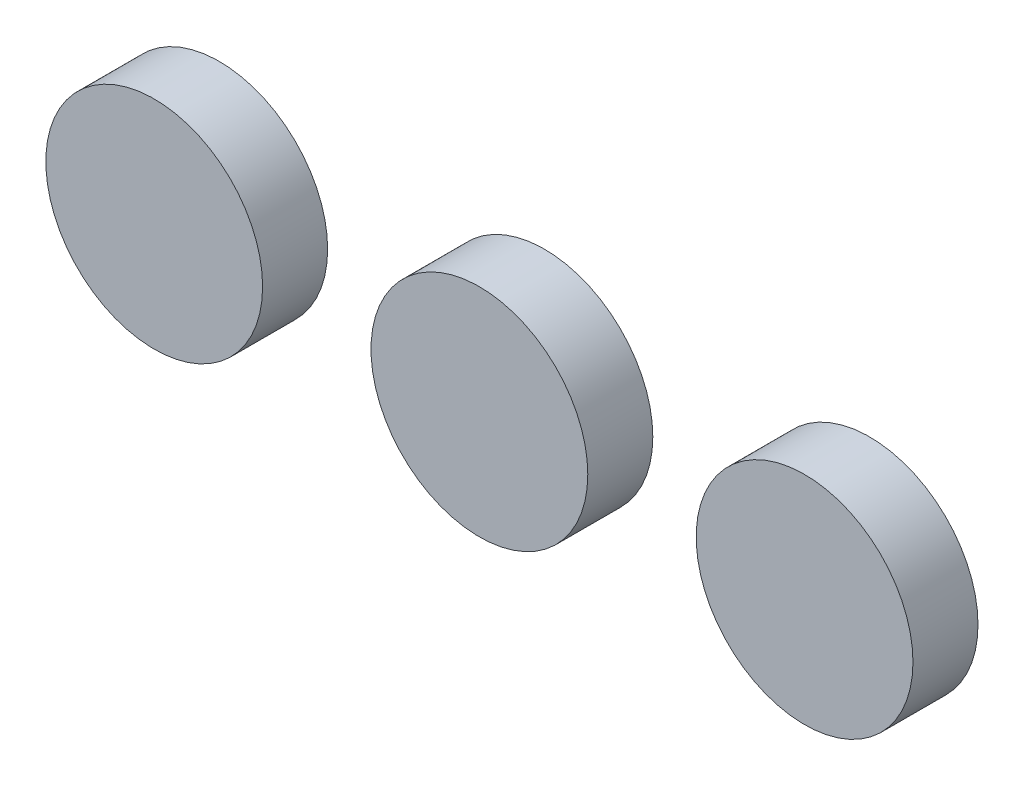
SolidWorks part; units mm, degrees
ref_plane "Front Plane" through (0, 0, 0) normal (0, 0, 1) x (1, 0, 0)
ref_plane "Top Plane" through (0, 0, 0) normal (0, 1, 0) x (1, 0, 0)
ref_plane "Right Plane" through (0, 0, 0) normal (1, 0, 0) x (0, 0, -1)
sketch "Sketch1" plane through (0, 0, 0) normal (0, 1, 0) x (1, 0, 0)
  line L1 (-200, -175) -> (200, -175) construction
  line L2 (-200, -175) -> (-200, 175) construction
  line L3 (-200, 175) -> (200, 175) construction
  line L4 (200, -175) -> (200, 175) construction
  line L5 (-200, -175) -> (200, 175) construction
  line L6 (-200, 175) -> (200, -175) construction
  point P0 (0, 0)
  dimension "D1" = 350
  dimension "D2" = 400
sketch "Sketch2" plane through (0, 0, 0) normal (0, 0, 1) x (1, 0, 0)
  line L0 (-200, 0) -> (-150, 0) construction
  line L1 (-150, 0) -> (-150, -100) construction
  line L2 (-200, 0) -> (200, 0) construction
  line L4 (200, 0) -> (150, 0) construction
  line L7 (-200, 0) -> (200, 0) construction
  line L8 (-150, -100) -> (150, -100) construction
  line L9 (0, 0) -> (0, -100) construction
  circle A0 centre (-150, -100) radius 50
  circle A1 centre (0, -100) radius 50
  circle A2 centre (150, -100) radius 50
ref_plane "Plane1" through (0, 0, 175) normal (0, 0, 1) x (1, 0, 0)
sketch "Sketch3" plane through (0, 0, 175) normal (0, 0, 1) x (1, 0, 0)
  line L0 (-150, 0) -> (-150, -100) construction
  line L1 (-150, 0) -> (-150, -100) construction
  line L2 (-150, -100) -> (150, -100) construction
  line L3 (-150, -100) -> (150, -100) construction
  line L4 (-150, 0) -> (-200, 0) construction
  circle A1 centre (150, -100) radius 50
  circle A2 centre (150, -100) radius 50
  circle A3 centre (0, -100) radius 50
  circle A4 centre (0, -100) radius 50
  circle A5 centre (-150, -100) radius 50
  circle A6 centre (-150, -100) radius 50
  dimension "D1" = 0
  dimension "D2" = 0
  dimension "D3" = 0
sketch "Sketch4" plane through (0, 0, 0) normal (0, 1, 0) x (1, 0, 0)
  line L0 (200, -175) -> (200, 175) construction
  line L1 (-200, -100) -> (200, -100) construction
  line L2 (-200, -100) -> (-200, 100) construction
  line L3 (-200, 100) -> (200, 100) construction
  line L4 (200, -100) -> (200, 100) construction
  line L5 (-200, -100) -> (200, 100) construction
  line L6 (-200, 100) -> (200, -100) construction
  point P0 (0, 0)
  dimension "D1" = 200
extrude "Boss-Extrude1" add sketch "Sketch3" against normal blind 30
ref_plane "Plane2" through (0, 0, 100) normal (0, 0, 1) x (1, 0, 0)
sketch "Sketch5" plane through (0, 0, 100) normal (0, 0, 1) x (1, 0, 0)
  line L0 (-150, -100) -> (-75, -30) construction
  line L1 (200, 0) -> (0, 0) construction
  line L2 (-200, 0) -> (200, 0) construction
  line L3 (-200, 0) -> (200, 0) construction
  line L4 (-150, -100) -> (150, -100) construction
  line L5 (0, -100) -> (0, 0) construction
  line L6 (0, 0) -> (-150, 0) construction
  line L7 (-75, 0) -> (-75, -30) construction
  line L8 (100, 0) -> (100, 50) construction
  line L9 (-75, -30) -> (100, -30) construction
  line L10 (100, -30) -> (100, 50) construction
  line L11 (100, -30) -> (150, -30) construction
  line L12 (150, -30) -> (150, -100) construction
  circle A2 centre (-150, -100) radius 20
  circle A3 centre (0, -100) radius 20
  circle A4 centre (150, -100) radius 20
  circle A5 centre (-75, -30) radius 20
  circle A6 centre (100, 50) radius 20
